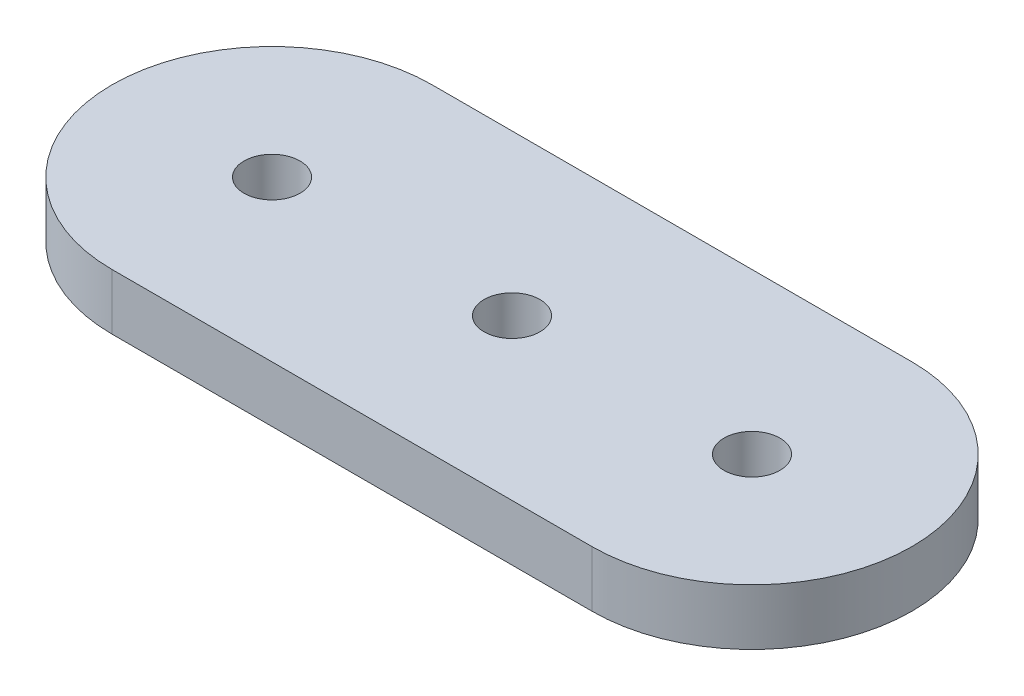
SolidWorks part; units mm, degrees
ref_plane "Спереди" through (0, 0, 0) normal (0, 0, 1) x (1, 0, 0)
ref_plane "Сверху" through (0, 0, 0) normal (0, 1, 0) x (1, 0, 0)
ref_plane "Справа" through (0, 0, 0) normal (1, 0, 0) x (0, 0, -1)
sketch "Эскиз1" plane through (0, 0, 0) normal (0, 1, 0) x (1, 0, 0)
  line L0 (0, 10) -> (30, 10)
  line L1 (0, -10) -> (30, -10)
  line L2 (0, 0) -> (30, 0) construction
  arc A0 (0, 10) -> (0, -10) centre (0, 0) ccw
  arc A1 (30, -10) -> (30, 10) centre (30, 0) ccw
  circle A2 centre (0, 0) radius 1.75
  circle A3 centre (30, 0) radius 1.75
  circle A4 centre (15, 0) radius 1.75
  dimension "D1" = 30
  dimension "D2" = 3.5
  dimension "D3" = 20
extrude "Бобышка-Вытянуть1" add sketch "Эскиз1" along normal blind 3.5
